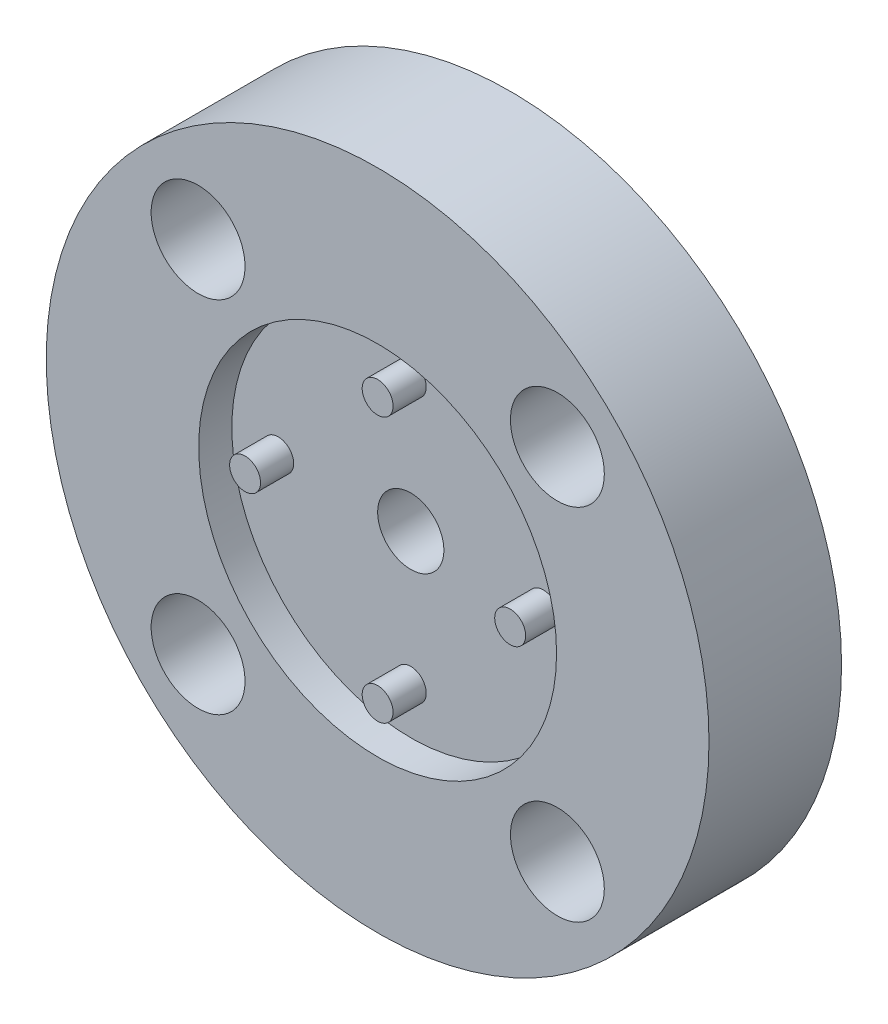
SolidWorks part; units mm, degrees
ref_plane "Front Plane" through (0, 0, 0) normal (0, 0, 1) x (1, 0, 0)
ref_plane "Top Plane" through (0, 0, 0) normal (0, 1, 0) x (1, 0, 0)
ref_plane "Right Plane" through (0, 0, 0) normal (1, 0, 0) x (0, 0, -1)
sketch "Sketch1" plane through (0, 0, 0) normal (0, 0, 1) x (1, 0, 0)
  line L0 (-8.1269, 8.1269) -> (8.1365, 8.1269) construction
  line L1 (6.633, 6.6252) -> (8.1365, 8.1269) construction
  circle A0 centre (0, 0) radius 15
  circle A1 centre (0, 0) radius 8 construction
  circle A2 centre (0, 0) radius 6 construction
  circle A3 centre (0, 6) radius 1
  circle A4 centre (6, 0) radius 1
  circle A5 centre (0, -6) radius 1
  circle A6 centre (-6, 0) radius 1
  circle A8 centre (8.1365, 8.1269) radius 2.125
  circle A9 centre (8.1365, -8.1365) radius 2.125
  circle A10 centre (-8.1269, -8.1365) radius 2.125
  circle A11 centre (-8.1269, 8.1269) radius 2.125
  circle A12 centre (0, 0) radius 11.5 construction
  circle A13 centre (0, 0) radius 1.5
  point P16 (0, 0)
  point P25 (0.0048, -0.0048)
  dimension "D1" = 30
  dimension "D2" = 16
  dimension "D3" = 12
  dimension "D4" = 2
  dimension "D6" = 4.25
  dimension "D9" = 3
  dimension "D7" = 11.5
  dimension "D5" = 4
  dimension "D8" = 4
extrude "Boss-Extrude1" add sketch "Sketch1" along normal blind 6 contours A3 | A4 | A0 A11 A10 A9 A8 A6 A5 A4 A3 | A6 | A5
sketch "Sketch2" plane through (0, 0, 6) normal (0, 0, 1) x (1, 0, 0)
  circle A0 centre (0, 6) radius 0.7
  circle A1 centre (6, 0) radius 0.7
  circle A2 centre (0, -6) radius 0.7
  circle A3 centre (-6, 0) radius 0.7
  circle A6 centre (0, 0) radius 8.1
  point P12 (0, 0)
  dimension "D1" = 1.4
  dimension "D3" = 16.2
  dimension "D2" = 4
extrude "Cut-Extrude1" cut sketch "Sketch2" against normal blind 1.5 contours A6 A0 A1 A2 A3
sketch "Sketch3" plane through (0, 0, 0) normal (0, 0, -1) x (-1, 0, 0)
  circle A0 centre (0, 0) radius 3
  dimension "D1" = 6
extrude "Cut-Extrude2" cut sketch "Sketch3" against normal blind 2
